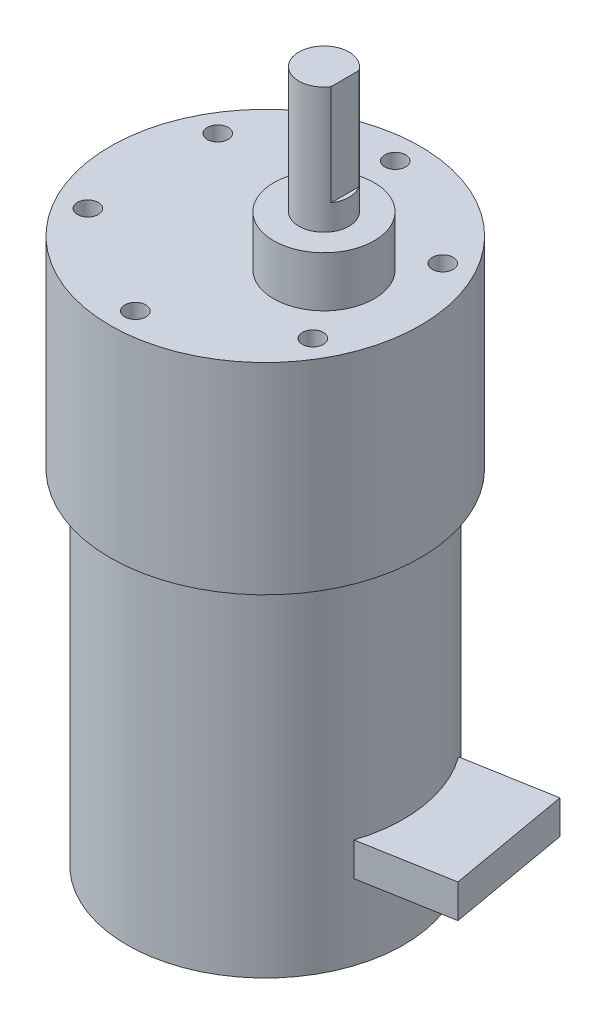
SolidWorks part; units mm, degrees
material "6061 Alloy"
ref_plane "Front Plane" through (0, 0, 0) normal (0, 0, 1) x (1, 0, 0)
ref_plane "Top Plane" through (0, 0, 0) normal (0, 1, 0) x (1, 0, 0)
ref_plane "Right Plane" through (0, 0, 0) normal (1, 0, 0) x (0, 0, -1)
sketch "Sketch1" plane through (0, 0, 0) normal (0, 1, 0) x (1, 0, 0)
  circle A0 centre (0, 0) radius 18.5
  dimension "D1" = 37
extrude "Boss-Extrude1" add sketch "Sketch1" along normal blind 24 contours A0
sketch "Sketch2" plane through (0, 0, 0) normal (0, -1, 0) x (1, 0, 0)
  circle A0 centre (0, 0) radius 16.5
  dimension "D1" = 33
extrude "Boss-Extrude2" add sketch "Sketch2" along normal blind 41
sketch "Sketch6" plane through (0, 24, 0) normal (0, 1, 0) x (1, 0, 0)
  circle A0 centre (0, 0) radius 15.5 construction
  circle A1 centre (13.4234, 7.75) radius 1.25
  circle A2 centre (0, 15.5) radius 1.25
  circle A3 centre (13.4234, -7.75) radius 1.25
  circle A4 centre (0, -15.5) radius 1.25
  circle A5 centre (-13.4234, -7.75) radius 1.25
  circle A6 centre (-13.4234, 7.75) radius 1.25
  point P18 (0, 0)
  dimension "D1" = 31
  dimension "D2" = 2.5
  dimension "D3" = 6
extrude "Cut-Extrude1" cut sketch "Sketch6" against normal blind 3.5
sketch "Sketch7" plane through (0, 24, 0) normal (0, 1, 0) x (1, 0, 0)
  circle A0 centre (7, 0) radius 6
  circle A1 centre (0, -15.5) radius 1.25 construction
  dimension "D1" = 12
  dimension "D2" = 7
extrude "Boss-Extrude5" add sketch "Sketch7" along normal blind 6
sketch "Sketch8" plane through (0, 30, 0) normal (0, 1, 0) x (1, 0, 0)
  circle A0 centre (7, 0) radius 3
  dimension "D1" = 6
extrude "Boss-Extrude6" add sketch "Sketch8" along normal blind 15
sketch "Sketch9" plane through (0, 45, 0) normal (0, 1, 0) x (1, 0, 0)
  line L0 (9.5, 1.6583) -> (9.5, -1.6583)
  arc A0 (9.5, -1.6583) -> (9.5, 1.6583) centre (7, 0) ccw
  dimension "D1" = 6
  dimension "D2" = 2.5
extrude "Cut-Extrude2" cut sketch "Sketch9" against normal blind 12
ref_plane "Plane1" through (16.2493, 0, -2.8652) normal (0.9848, 0, -0.1736) x (0, 1, 0)
sketch "Sketch3" plane through (16.2493, 0, -2.8652) normal (0.9848, 0, -0.1736) x (0, 1, 0)
  line L6 (-28, 7.7544) -> (-32, 7.7544)
  line L7 (-28, 7.7544) -> (-28, -7.2456)
  line L8 (-28, -7.2456) -> (-32, -7.2456)
  line L9 (-32, 7.7544) -> (-32, -7.2456)
  line L10 (-41, 16.5) -> (-41, -16.5) construction
  dimension "D1" = 15
  dimension "D2" = 4
  dimension "D3" = 9
extrude "Boss-Extrude4" add sketch "Sketch3" against normal mid plane 17.526
